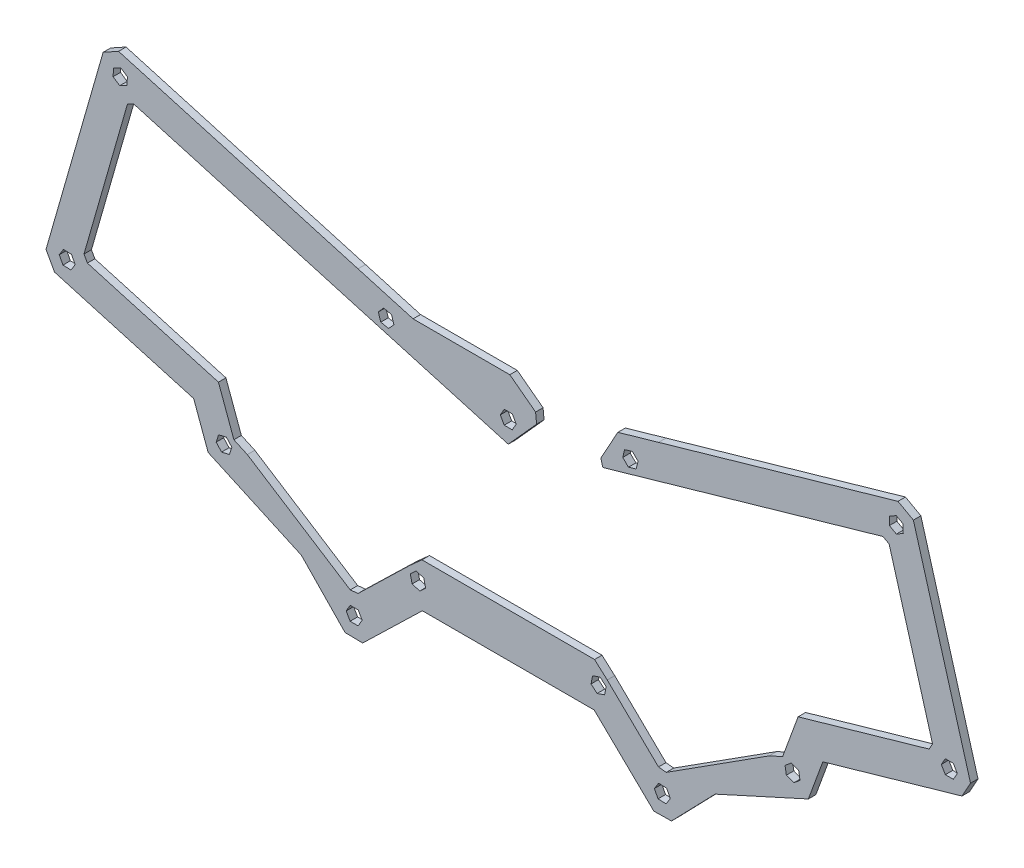
SolidWorks part; units mm, degrees
ref_plane "Plan de face" through (0, 0, 0) normal (0, 0, 1) x (1, 0, 0)
ref_plane "Plan de dessus" through (0, 0, 0) normal (0, 1, 0) x (1, 0, 0)
ref_plane "Plan de droite" through (0, 0, 0) normal (1, 0, 0) x (0, 0, -1)
sketch "Esquisse1" plane through (0, 0, 0) normal (0, 0, 1) x (1, 0, 0)
  line L0 (-121.6461, -32.0475) -> (-108.1875, -28.1884) construction
  line L1 (-108.1875, -28.1884) -> (-104.3283, -41.647) construction
  line L2 (-104.3283, -41.647) -> (-117.7869, -45.5062) construction
  line L3 (-117.7869, -45.5062) -> (-121.6461, -32.0475) construction
  line L4 (-100.1763, -37.9855) -> (-104.0355, -24.5269) construction
  line L5 (-104.0355, -24.5269) -> (-90.5769, -20.6677) construction
  line L6 (-90.5769, -20.6677) -> (-86.7177, -34.1263) construction
  line L7 (-86.7177, -34.1263) -> (-100.1763, -37.9855) construction
  line L8 (-82.5657, -30.4649) -> (-86.4249, -17.0063) construction
  line L9 (-86.4249, -17.0063) -> (-72.9663, -13.1471) construction
  line L10 (-72.9663, -13.1471) -> (-69.1071, -26.6057) construction
  line L11 (-69.1071, -26.6057) -> (-82.5657, -30.4649) construction
  line L12 (-63.6458, -27.5106) -> (-67.505, -14.0519) construction
  line L13 (-67.505, -14.0519) -> (-54.0463, -10.1927) construction
  line L14 (-54.0463, -10.1927) -> (-50.1872, -23.6514) construction
  line L15 (-50.1872, -23.6514) -> (-63.6458, -27.5106) construction
  line L16 (-44.0711, -26.8394) -> (-47.9303, -13.3808) construction
  line L17 (-47.9303, -13.3808) -> (-34.4717, -9.5216) construction
  line L18 (-34.4717, -9.5216) -> (-30.6125, -22.9802) construction
  line L19 (-30.6125, -22.9802) -> (-44.0711, -26.8394) construction
  line L20 (-25.8054, -21.6018) -> (-29.6646, -8.1432) construction
  line L21 (-29.6646, -8.1432) -> (-16.206, -4.284)
  line L22 (-16.206, -4.284) -> (-12.3468, -17.7426)
  line L23 (-12.3468, -17.7426) -> (-25.8054, -21.6018) construction
  line L24 (-116.4086, -50.3128) -> (-102.95, -46.4536) construction
  line L25 (-102.95, -46.4536) -> (-99.0908, -59.9122) construction
  line L26 (-99.0908, -59.9122) -> (-112.5494, -63.7714) construction
  line L27 (-112.5494, -63.7714) -> (-116.4086, -50.3128) construction
  line L28 (-98.798, -42.7922) -> (-85.3394, -38.933) construction
  line L29 (-85.3394, -38.933) -> (-81.4802, -52.3916) construction
  line L30 (-81.4802, -52.3916) -> (-94.9388, -56.2508) construction
  line L31 (-94.9388, -56.2508) -> (-98.798, -42.7922) construction
  line L32 (-81.1874, -35.2715) -> (-67.7288, -31.4123) construction
  line L33 (-67.7288, -31.4123) -> (-63.8696, -44.8709) construction
  line L34 (-63.8696, -44.8709) -> (-77.3282, -48.7301) construction
  line L35 (-77.3282, -48.7301) -> (-81.1874, -35.2715) construction
  line L36 (-62.2675, -32.3172) -> (-48.8089, -28.458) construction
  line L37 (-48.8089, -28.458) -> (-44.9497, -41.9166) construction
  line L38 (-44.9497, -41.9166) -> (-58.4083, -45.7758) construction
  line L39 (-58.4083, -45.7758) -> (-62.2675, -32.3172) construction
  line L40 (-42.6928, -31.646) -> (-29.2342, -27.7869) construction
  line L41 (-29.2342, -27.7869) -> (-25.375, -41.2455) construction
  line L42 (-25.375, -41.2455) -> (-38.8336, -45.1047) construction
  line L43 (-38.8336, -45.1047) -> (-42.6928, -31.646) construction
  line L44 (-24.4271, -26.4084) -> (-10.9685, -22.5492) construction
  line L45 (-10.9685, -22.5492) -> (-7.1093, -36.0078) construction
  line L46 (-7.1093, -36.0078) -> (-20.5679, -39.867) construction
  line L47 (-20.5679, -39.867) -> (-24.4271, -26.4084) construction
  line L48 (-19.1896, -44.6737) -> (-5.731, -40.8145) construction
  line L49 (-5.731, -40.8145) -> (-1.8718, -54.2731) construction
  line L50 (-1.8718, -54.2731) -> (-15.3304, -58.1323) construction
  line L51 (-15.3304, -58.1323) -> (-19.1896, -44.6737) construction
  line L52 (-37.4554, -49.9113) -> (-23.9967, -46.0521) construction
  line L53 (-23.9967, -46.0521) -> (-20.1376, -59.5107) construction
  line L54 (-20.1376, -59.5107) -> (-33.5962, -63.3699) construction
  line L55 (-33.5962, -63.3699) -> (-37.4554, -49.9113) construction
  line L56 (-57.03, -50.5825) -> (-43.5714, -46.7233) construction
  line L57 (-43.5714, -46.7233) -> (-39.7122, -60.1819) construction
  line L58 (-39.7122, -60.1819) -> (-53.1708, -64.0411) construction
  line L59 (-53.1708, -64.0411) -> (-57.03, -50.5825) construction
  line L60 (-75.9499, -53.5368) -> (-62.4913, -49.6776) construction
  line L61 (-62.4913, -49.6776) -> (-58.6321, -63.1362) construction
  line L62 (-58.6321, -63.1362) -> (-72.0908, -66.9954) construction
  line L63 (-72.0908, -66.9954) -> (-75.9499, -53.5368) construction
  line L64 (-93.5605, -61.0574) -> (-80.1019, -57.1982) construction
  line L65 (-80.1019, -57.1982) -> (-76.2427, -70.6569) construction
  line L66 (-76.2427, -70.6569) -> (-89.7013, -74.516) construction
  line L67 (-89.7013, -74.516) -> (-93.5605, -61.0574) construction
  line L68 (-111.1711, -68.5781) -> (-97.7125, -64.7189) construction
  line L69 (-97.7125, -64.7189) -> (-93.8533, -78.1775) construction
  line L70 (-93.8533, -78.1775) -> (-107.3119, -82.0367) construction
  line L71 (-107.3119, -82.0367) -> (-111.1711, -68.5781) construction
  line L72 (-79.0181, -77.3048) -> (-65.5595, -73.4456) construction
  line L73 (-65.5595, -73.4456) -> (-61.7003, -86.9042) construction
  line L74 (-61.7003, -86.9042) -> (-75.1589, -90.7634) construction
  line L75 (-75.1589, -90.7634) -> (-79.0181, -77.3048) construction
  line L76 (-99.4001, -88.1351) -> (-87.3916, -80.9362) construction
  line L77 (-87.3916, -80.9362) -> (-80.1927, -92.9448) construction
  line L78 (-80.1927, -92.9448) -> (-92.2012, -100.1436) construction
  line L79 (-92.2012, -100.1436) -> (-99.4001, -88.1351) construction
  line L80 (-120.0498, -100.4367) -> (-110.317, -90.3719) construction
  line L81 (-110.317, -90.3719) -> (-100.2522, -100.1047) construction
  line L82 (-100.2522, -100.1047) -> (-109.985, -110.1695) construction
  line L83 (-109.985, -110.1695) -> (-120.0498, -100.4367) construction
  line L86 (0.634, -55.7756) -> (-52.9527, -71.1413) construction
  line L89 (-59.2205, -88.2424) -> (-52.9527, -71.1413) construction
  line L96 (-93.4066, -103.0586) -> (-59.4637, -88.3612) construction
  line L97 (-105.418, -115.2057) -> (-93.9754, -103.3509) construction
  line L98 (-126.5332, -96.9919) -> (-107.5003, -115.385) construction
  line L99 (-167.7972, -50.1766) -> (-183.2082, -64.014) construction
  line L100 (-106.3822, -25.4572) -> (-123.6848, -30.4187) construction
  line L101 (-72.1178, -10.6906) -> (-88.4663, -15.3784) construction
  line L102 (-53.2337, -7.6163) -> (-70.5393, -12.5786) construction
  line L103 (-33.6604, -6.9452) -> (-50.9661, -11.9075) construction
  line L104 (-15.3965, -1.7081) -> (-31.745, -6.396) construction
  line L105 (0.5403, -55.2132) -> (-14.6896, -2.0999) construction
  line L106 (-16.199, -60.6113) -> (0.1495, -55.9235) construction
  line L107 (-52.7198, -71.0835) -> (-18.1144, -61.1606) construction
  line L108 (-59.1184, -88.0534) -> (-52.9674, -71.2752) construction
  line L109 (-183.2082, -64.014) -> (-173.1824, -64.9357) construction
  line L113 (-102.2678, -134.438) -> (-84.7238, -116.3191)
  line L114 (-84.7238, -116.3191) -> (-47.2969, -99.2981)
  line L115 (-47.2969, -99.2981) -> (-41.4917, -83.4594)
  line L116 (14.3812, -67.4381) -> (-41.4917, -83.4594)
  line L117 (17.8093, -61.2536) -> (-5.1371, 18.7701)
  line L122 (-11.3217, 22.1985) -> (-107.4545, -5.3614)
  line L129 (-167.7953, -27.6055) -> (-167.7953, -64.7189) construction
  line L130 (-242.0685, -103.8419) -> (-276.37, -88.2424) construction
  line L131 (-229.5108, -116.8112) -> (-242.0685, -103.8419) construction
  line L138 (-208.9328, -96.8551) -> (-229.5108, -116.8112) construction
  line L139 (-225.5107, -79.6567) -> (-208.9328, -96.8551) construction
  line L140 (-109.3352, -134.5492) -> (-102.2678, -134.438)
  line L142 (-5.1371, 18.7701) -> (-11.3217, 22.1985)
  line L143 (-211.4691, -30.6868) -> (-225.5107, -79.6567) construction
  line L147 (-114.18, -7.2899) -> (-107.4545, -5.3614)
  line L148 (-114.18, -7.2899) -> (-123.7936, -10.0465)
  line L154 (-4.3102, 15.8863) -> (-127.3606, -19.3904) construction
  line L155 (-131.531, -101.8802) -> (-105.9239, -126.7133) construction
  line L156 (-105.9239, -126.7133) -> (-89.4162, -109.6646) construction
  line L157 (-127.3539, -97.573) -> (-105.9069, -118.3718) construction
  line L158 (-105.9069, -118.3718) -> (-63.5032, -91.2886) construction
  line L159 (-63.5032, -91.2886) -> (-58.4256, -88.9794) construction
  line L160 (-58.4256, -88.9794) -> (-52.1886, -71.9625) construction
  line L161 (1.8709, -56.4612) -> (-52.1886, -71.9625) construction
  line L162 (1.8709, -56.4612) -> (-14.1861, -0.4639) construction
  line L163 (-14.1861, -0.4639) -> (-50.7166, -10.9388) construction
  line L164 (-50.7166, -10.9388) -> (-52.026, -6.3725) construction
  line L165 (-52.026, -6.3725) -> (-70.2913, -11.61) construction
  line L166 (-70.2913, -11.61) -> (-70.911, -9.4488) construction
  line L167 (-70.911, -9.4488) -> (-90.1377, -14.9608) construction
  line L168 (-90.1377, -14.9608) -> (-89.5177, -17.1231) construction
  line L169 (-89.5177, -17.1231) -> (-107.783, -22.3606) construction
  line L170 (-107.783, -22.3606) -> (-107.0938, -24.7639) construction
  line L171 (-107.0938, -24.7639) -> (-125.3583, -30.0011) construction
  line L172 (-125.3583, -30.0011) -> (-111.0411, -79.9324) construction
  line L173 (-110.7998, -78.9627) -> (-127.3777, -96.1611) construction
  line L174 (-89.4162, -109.6646) -> (-53.6562, -93.4017) construction
  line L175 (-53.6562, -93.4017) -> (-47.6042, -76.8897) construction
  line L176 (9.2923, -60.5749) -> (-47.6042, -76.8897) construction
  line L177 (9.2923, -60.5749) -> (-12.0005, 13.6817) construction
  line L178 (-229.7336, -25.4495) -> (-211.4691, -30.6868) construction
  line L179 (-229.0444, -23.0462) -> (-229.7336, -25.4495) construction
  line L180 (-173.1824, -64.9357) -> (-167.7972, -60.1004) construction
  line L181 (-247.3097, -17.8087) -> (-229.0444, -23.0462) construction
  line L185 (17.8093, -61.2536) -> (14.3812, -67.4381)
  line L186 (-183.2987, -65.7677) -> (-173.2729, -66.6895) construction
  line L187 (-173.2729, -66.6895) -> (-167.8052, -74.7882) construction
  line L190 (-246.6897, -15.6465) -> (-247.3097, -17.8087) construction
  line L191 (-263.9939, -10.6857) -> (-246.6897, -15.6465) construction
  line L192 (-264.6136, -12.8469) -> (-263.9939, -10.6857) construction
  line L193 (-282.8789, -7.6094) -> (-264.6136, -12.8469) construction
  line L194 (-284.1883, -12.1757) -> (-282.8789, -7.6094) construction
  line L195 (-320.7188, -1.7008) -> (-284.1883, -12.1757) construction
  line L196 (-336.2245, -55.7756) -> (-320.7188, -1.7008) construction
  line L197 (-183.2987, -65.7677) -> (-167.8052, -88.0782) construction
  line L198 (-181.8414, -71.5322) -> (-174.8684, -81.0171) construction
  line L199 (-174.8684, -81.0171) -> (-178.3549, -83.9622) construction
  line L200 (-344.8828, -60.5749) -> (-323.5901, 13.6817) construction
  line L201 (-344.8828, -60.5749) -> (-287.9863, -76.8897) construction
  line L202 (-281.9343, -93.4017) -> (-287.9863, -76.8897) construction
  line L203 (-246.1743, -109.6646) -> (-281.9343, -93.4017) construction
  line L204 (-224.7907, -78.9627) -> (-208.2128, -96.1611) construction
  line L205 (-210.2322, -30.0011) -> (-224.5494, -79.9324) construction
  line L206 (-228.4967, -24.7639) -> (-210.2322, -30.0011) construction
  line L207 (-227.8075, -22.3606) -> (-228.4967, -24.7639) construction
  line L208 (-246.0728, -17.1231) -> (-227.8075, -22.3606) construction
  line L209 (-245.4528, -14.9608) -> (-246.0728, -17.1231) construction
  line L210 (-264.6796, -9.4488) -> (-245.4528, -14.9608) construction
  line L211 (-265.2993, -11.61) -> (-264.6796, -9.4488) construction
  line L212 (-283.5645, -6.3725) -> (-265.2993, -11.61) construction
  line L213 (-284.8739, -10.9388) -> (-283.5645, -6.3725) construction
  line L217 (0.634, -55.7756) -> (-14.8717, -1.7008) construction
  line L220 (-14.8717, -1.7008) -> (-51.4022, -12.1757) construction
  line L221 (-51.4022, -12.1757) -> (-52.7116, -7.6094) construction
  line L222 (-52.7116, -7.6094) -> (-70.9769, -12.8469) construction
  line L223 (-70.9769, -12.8469) -> (-71.5966, -10.6857) construction
  line L224 (-71.5966, -10.6857) -> (-88.9008, -15.6465) construction
  line L225 (-88.9008, -15.6465) -> (-88.2808, -17.8087) construction
  line L226 (-88.2808, -17.8087) -> (-106.5461, -23.0462) construction
  line L227 (-106.5461, -23.0462) -> (-105.8569, -25.4495) construction
  line L228 (-105.8569, -25.4495) -> (-124.1214, -30.6868) construction
  line L231 (-124.1214, -30.6868) -> (-110.0799, -79.6567) construction
  line L232 (-110.0799, -79.6567) -> (-126.6577, -96.8551) construction
  line L233 (-126.6577, -96.8551) -> (-106.0797, -116.8112) construction
  line L234 (-106.0797, -116.8112) -> (-93.522, -103.8419) construction
  line L235 (-93.522, -103.8419) -> (-59.2205, -88.2424) construction
  line L236 (-321.4044, -0.4639) -> (-284.8739, -10.9388) construction
  line L237 (-337.4614, -56.4612) -> (-321.4044, -0.4639) construction
  line L238 (-337.4614, -56.4612) -> (-283.4019, -71.9625) construction
  line L239 (-277.1649, -88.9794) -> (-283.4019, -71.9625) construction
  line L240 (-272.0873, -91.2886) -> (-277.1649, -88.9794) construction
  line L241 (-229.6837, -118.3718) -> (-272.0873, -91.2886) construction
  line L242 (-208.2366, -97.573) -> (-229.6837, -118.3718) construction
  line L243 (-229.6666, -126.7133) -> (-246.1743, -109.6646) construction
  line L244 (-204.0596, -101.8802) -> (-229.6666, -126.7133) construction
  line L245 (-331.2803, 15.8863) -> (-208.2299, -19.3904) construction
  line L246 (-178.3549, -83.9622) -> (-185.8788, -75.0552) construction
  line L247 (-185.8788, -75.0552) -> (-181.8414, -71.5322) construction
  line L248 (-176.7625, -46.6332) -> (-185.5498, -54.5291) construction
  line L249 (-185.5498, -54.5291) -> (-181.1562, -59.4188) construction
  line L250 (-181.1562, -59.4188) -> (-172.3689, -51.5229) construction
  line L251 (-276.4721, -88.0534) -> (-282.6232, -71.2752) construction
  line L252 (-282.8707, -71.0835) -> (-317.4761, -61.1606) construction
  line L253 (-319.3915, -60.6113) -> (-335.74, -55.9235) construction
  line L254 (-336.1309, -55.2132) -> (-320.9009, -2.0999) construction
  line L255 (-320.194, -1.7081) -> (-303.8455, -6.396) construction
  line L256 (-301.9301, -6.9452) -> (-284.6245, -11.9075) construction
  line L257 (-282.3568, -7.6163) -> (-265.0512, -12.5786) construction
  line L258 (-263.4727, -10.6906) -> (-247.1242, -15.3784) construction
  line L259 (-229.2083, -25.4572) -> (-211.9057, -30.4187) construction
  line L260 (-172.3689, -51.5229) -> (-176.7625, -46.6332) construction
  line L261 (-209.0573, -96.9919) -> (-228.0902, -115.385) construction
  line L262 (-230.1725, -115.2057) -> (-241.6151, -103.3509) construction
  line L263 (-242.1839, -103.0586) -> (-276.1268, -88.3612) construction
  line L264 (-276.37, -88.2424) -> (-282.6379, -71.1413) construction
  line L265 (-336.2245, -55.7756) -> (-282.6379, -71.1413) construction
  line L268 (-353.3998, -61.2536) -> (-349.9717, -67.4381)
  line L274 (-221.4105, -7.2899) -> (-206.0252, -11.7015)
  line L275 (-221.4105, -7.2899) -> (-228.136, -5.3614)
  line L276 (-330.4534, 18.7701) -> (-324.2688, 22.1985)
  line L277 (-226.2553, -134.5492) -> (-233.3227, -134.438)
  line L281 (-324.2688, 22.1985) -> (-228.136, -5.3614)
  line L282 (-353.3998, -61.2536) -> (-330.4534, 18.7701)
  line L283 (-349.9717, -67.4381) -> (-294.0988, -83.4594)
  line L284 (-288.2936, -99.2981) -> (-294.0988, -83.4594)
  line L285 (-250.8667, -116.3191) -> (-288.2936, -99.2981)
  line L286 (-233.3227, -134.438) -> (-250.8667, -116.3191)
  line L288 (-225.6055, -110.1695) -> (-215.5407, -100.4367) construction
  line L289 (-235.3383, -100.1047) -> (-225.6055, -110.1695) construction
  line L290 (-225.2735, -90.3719) -> (-235.3383, -100.1047) construction
  line L291 (-215.5407, -100.4367) -> (-225.2735, -90.3719) construction
  line L292 (-243.3893, -100.1436) -> (-236.1904, -88.1351) construction
  line L293 (-255.3978, -92.9448) -> (-243.3893, -100.1436) construction
  line L294 (-248.1989, -80.9362) -> (-255.3978, -92.9448) construction
  line L295 (-236.1904, -88.1351) -> (-248.1989, -80.9362) construction
  line L296 (-260.4316, -90.7634) -> (-256.5724, -77.3048) construction
  line L297 (-273.8902, -86.9042) -> (-260.4316, -90.7634) construction
  line L298 (-270.031, -73.4456) -> (-273.8902, -86.9042) construction
  line L299 (-256.5724, -77.3048) -> (-270.031, -73.4456) construction
  line L300 (-228.2786, -82.0367) -> (-224.4194, -68.5781) construction
  line L301 (-241.7372, -78.1775) -> (-228.2786, -82.0367) construction
  line L302 (-237.878, -64.7189) -> (-241.7372, -78.1775) construction
  line L303 (-224.4194, -68.5781) -> (-237.878, -64.7189) construction
  line L304 (-245.8892, -74.516) -> (-242.03, -61.0574) construction
  line L305 (-259.3478, -70.6569) -> (-245.8892, -74.516) construction
  line L306 (-255.4886, -57.1982) -> (-259.3478, -70.6569) construction
  line L307 (-242.03, -61.0574) -> (-255.4886, -57.1982) construction
  line L308 (-263.4998, -66.9954) -> (-259.6406, -53.5368) construction
  line L309 (-276.9584, -63.1362) -> (-263.4998, -66.9954) construction
  line L310 (-273.0992, -49.6776) -> (-276.9584, -63.1362) construction
  line L311 (-259.6406, -53.5368) -> (-273.0992, -49.6776)
  line L312 (-282.4197, -64.0411) -> (-278.5605, -50.5825) construction
  line L313 (-295.8783, -60.1819) -> (-282.4197, -64.0411) construction
  line L314 (-292.0191, -46.7233) -> (-295.8783, -60.1819) construction
  line L315 (-278.5605, -50.5825) -> (-292.0191, -46.7233) construction
  line L316 (-301.9944, -63.3699) -> (-298.1352, -49.9113) construction
  line L317 (-315.453, -59.5107) -> (-301.9944, -63.3699) construction
  line L318 (-311.5938, -46.0521) -> (-315.453, -59.5107) construction
  line L319 (-298.1352, -49.9113) -> (-311.5938, -46.0521) construction
  line L320 (-320.2601, -58.1323) -> (-316.4009, -44.6737) construction
  line L321 (-333.7187, -54.2731) -> (-320.2601, -58.1323) construction
  line L322 (-329.8595, -40.8145) -> (-333.7187, -54.2731) construction
  line L323 (-316.4009, -44.6737) -> (-329.8595, -40.8145) construction
  line L324 (-315.0226, -39.867) -> (-311.1634, -26.4084) construction
  line L325 (-328.4812, -36.0078) -> (-315.0226, -39.867) construction
  line L326 (-324.622, -22.5492) -> (-328.4812, -36.0078) construction
  line L327 (-311.1634, -26.4084) -> (-324.622, -22.5492) construction
  line L328 (-296.7569, -45.1047) -> (-292.8977, -31.646) construction
  line L329 (-310.2155, -41.2455) -> (-296.7569, -45.1047) construction
  line L330 (-306.3563, -27.7869) -> (-310.2155, -41.2455) construction
  line L331 (-292.8977, -31.646) -> (-306.3563, -27.7869) construction
  line L332 (-277.1822, -45.7758) -> (-273.323, -32.3172) construction
  line L333 (-290.6408, -41.9166) -> (-277.1822, -45.7758) construction
  line L334 (-286.7817, -28.458) -> (-290.6408, -41.9166) construction
  line L335 (-273.323, -32.3172) -> (-286.7817, -28.458) construction
  line L336 (-258.2623, -48.7301) -> (-254.4031, -35.2715) construction
  line L337 (-271.7209, -44.8709) -> (-258.2623, -48.7301) construction
  line L338 (-267.8617, -31.4123) -> (-271.7209, -44.8709) construction
  line L339 (-254.4031, -35.2715) -> (-267.8617, -31.4123) construction
  line L340 (-240.6517, -56.2508) -> (-236.7925, -42.7922) construction
  line L341 (-254.1103, -52.3916) -> (-240.6517, -56.2508) construction
  line L342 (-250.2511, -38.933) -> (-254.1103, -52.3916) construction
  line L343 (-236.7925, -42.7922) -> (-250.2511, -38.933) construction
  line L344 (-223.0411, -63.7714) -> (-219.1819, -50.3128) construction
  line L345 (-236.4997, -59.9122) -> (-223.0411, -63.7714) construction
  line L346 (-232.6405, -46.4536) -> (-236.4997, -59.9122) construction
  line L347 (-219.1819, -50.3128) -> (-232.6405, -46.4536) construction
  line L348 (-323.2438, -17.7426) -> (-309.7851, -21.6018) construction
  line L349 (-319.3846, -4.284) -> (-323.2438, -17.7426) construction
  line L350 (-305.926, -8.1432) -> (-319.3846, -4.284) construction
  line L351 (-309.7851, -21.6018) -> (-305.926, -8.1432) construction
  line L352 (-304.978, -22.9802) -> (-291.5194, -26.8394) construction
  line L353 (-301.1188, -9.5216) -> (-304.978, -22.9802) construction
  line L354 (-287.6602, -13.3808) -> (-301.1188, -9.5216) construction
  line L355 (-291.5194, -26.8394) -> (-287.6602, -13.3808) construction
  line L356 (-285.4034, -23.6514) -> (-271.9448, -27.5106) construction
  line L357 (-281.5442, -10.1927) -> (-285.4034, -23.6514) construction
  line L358 (-268.0856, -14.0519) -> (-281.5442, -10.1927) construction
  line L359 (-271.9448, -27.5106) -> (-268.0856, -14.0519) construction
  line L360 (-266.4834, -26.6057) -> (-253.0248, -30.4649) construction
  line L361 (-262.6242, -13.1471) -> (-266.4834, -26.6057) construction
  line L362 (-249.1656, -17.0063) -> (-262.6242, -13.1471) construction
  line L363 (-253.0248, -30.4649) -> (-249.1656, -17.0063) construction
  line L364 (-248.8728, -34.1263) -> (-235.4142, -37.9855) construction
  line L365 (-245.0136, -20.6677) -> (-248.8728, -34.1263) construction
  line L366 (-231.555, -24.5269) -> (-245.0136, -20.6677) construction
  line L367 (-235.4142, -37.9855) -> (-231.555, -24.5269) construction
  line L368 (-217.8036, -45.5062) -> (-213.9444, -32.0475) construction
  line L369 (-231.2622, -41.647) -> (-217.8036, -45.5062) construction
  line L370 (-227.4031, -28.1884) -> (-231.2622, -41.647) construction
  line L371 (-213.9444, -32.0475) -> (-227.4031, -28.1884) construction
  line L372 (-226.2553, -134.5492) -> (-202.2968, -111.3509)
  line L373 (-109.3352, -134.5492) -> (-133.2937, -111.3509)
  line L374 (-141.5559, -103.3509) -> (-194.0347, -103.3509) construction
  line L375 (-167.7972, -50.1766) -> (-152.3861, -64.014) construction
  line L376 (-162.4119, -64.9357) -> (-167.7972, -60.1004) construction
  line L377 (-162.3376, -66.6895) -> (-167.8052, -74.7882) construction
  line L378 (-152.3118, -65.7677) -> (-167.8052, -88.0782) construction
  line L379 (-163.2254, -51.5229) -> (-158.8318, -46.6332) construction
  line L380 (-154.4381, -59.4188) -> (-163.2254, -51.5229) construction
  line L381 (-150.0445, -54.5291) -> (-154.4381, -59.4188) construction
  line L382 (-158.8318, -46.6332) -> (-150.0445, -54.5291) construction
  line L383 (-149.7316, -75.0552) -> (-153.7691, -71.5322) construction
  line L384 (-157.2555, -83.9622) -> (-149.7316, -75.0552) construction
  line L385 (-160.742, -81.0171) -> (-157.2555, -83.9622) construction
  line L386 (-153.7691, -71.5322) -> (-160.742, -81.0171) construction
  line L387 (-152.3118, -65.7677) -> (-162.3376, -66.6895) construction
  line L388 (-152.3861, -64.014) -> (-162.4119, -64.9357) construction
  line L389 (-206.0252, -11.7015) -> (-129.5654, -11.7015) construction
  line L390 (-119.0708, -62.7964) -> (-130.6498, -22.4155) construction
  line L391 (-123.5545, -47.16) -> (-127.4136, -33.7014) construction
  line L392 (-120.442, -65.2702) -> (-138.2688, -70.3819) construction
  line L393 (-140.7426, -69.0107) -> (-154.4194, -21.3141) construction
  line L394 (-167.1758, -11.7015) -> (-206.0252, -11.7015)
  line L395 (-156.8153, -19.5087) -> (-167.1758, -11.7015)
  line L396 (-123.7936, -10.0465) -> (-130.6498, -22.4155)
  line L397 (-138.2688, -70.3819) -> (-140.7426, -69.0107) construction
  line L398 (-119.0708, -62.7964) -> (-120.442, -65.2702) construction
  line L399 (-129.5654, -11.7015) -> (-123.7936, -10.0465) construction
  line L400 (-207.5404, -98.2908) -> (-228.1196, -118.248)
  line L401 (-231.2409, -118.5638) -> (-272.5658, -92.1695)
  line L402 (-272.5658, -92.1695) -> (-277.9598, -89.7165)
  line L403 (-277.9598, -89.7165) -> (-284.166, -72.7837)
  line L404 (-336.7758, -57.6981) -> (-284.166, -72.7837)
  line L405 (-338.147, -55.2243) -> (-320.7131, 5.5749)
  line L406 (-223.5881, -80.208) -> (-202.439, -93.7159) construction
  line L407 (-202.439, -93.7159) -> (-207.5404, -98.2908)
  line L408 (-17.3512, 6.9463) -> (-127.905, -24.7479)
  line L409 (2.5565, -55.2243) -> (-14.8774, 5.5749)
  line L410 (-318.2393, 6.9463) -> (-167.7953, -36.1838)
  line L411 (1.1853, -57.6981) -> (-51.4245, -72.7837)
  line L412 (-57.6307, -89.7165) -> (-51.4245, -72.7837)
  line L413 (-63.0247, -92.1695) -> (-57.6307, -89.7165)
  line L414 (-104.3497, -118.5638) -> (-63.0247, -92.1695)
  line L415 (-207.6856, -24.7479) -> (-223.5881, -80.208) construction
  line L416 (-338.6983, -57.1468) -> (-322.0901, 0.773) construction
  line L417 (-265.3652, -8.212) -> (-244.2159, -14.2752) construction
  line L418 (-208.9953, -29.3155) -> (-223.5881, -80.208) construction
  line L419 (-227.2598, -24.0783) -> (-208.9953, -29.3155) construction
  line L420 (-226.5706, -21.6749) -> (-227.2598, -24.0783) construction
  line L421 (-244.8359, -16.4375) -> (-226.5706, -21.6749) construction
  line L422 (-244.2159, -14.2752) -> (-244.8359, -16.4375) construction
  line L423 (-265.9849, -10.3731) -> (-265.3652, -8.212) construction
  line L424 (-284.2502, -5.1356) -> (-265.9849, -10.3731) construction
  line L425 (-285.5595, -9.7019) -> (-284.2502, -5.1356) construction
  line L426 (-322.0901, 0.773) -> (-285.5595, -9.7019) construction
  line L427 (-128.0501, -98.2908) -> (-107.4709, -118.248)
  line L428 (-133.1515, -93.7159) -> (-128.0501, -98.2908)
  line L429 (-127.905, -24.7479) -> (-167.7953, -36.1862) construction
  line L430 (-129.8233, -25.2979) -> (-130.6498, -22.4155)
  line L431 (-202.439, -93.7159) -> (-133.1515, -93.7159)
  line L432 (-167.7953, -36.1838) -> (-156.4257, -23.5445)
  line L433 (-129.8233, -25.2979) -> (-127.905, -24.7479)
  line L434 (-156.4257, -23.5445) -> (-156.8153, -19.5087)
  line L435 (-320.7131, 5.5749) -> (-318.2393, 6.9463)
  line L436 (-338.6983, -57.1468) -> (-284.166, -72.7837) construction
  line L437 (-338.147, -55.2243) -> (-336.7758, -57.6981)
  line L438 (-207.5404, -98.2908) -> (-229.5553, -119.6404) construction
  line L439 (-229.5553, -119.6404) -> (-272.5658, -92.1695) construction
  line L440 (-228.1196, -118.248) -> (-231.2409, -118.5638)
  line L441 (-107.4709, -118.248) -> (-104.3497, -118.5638)
  line L442 (2.5565, -55.2243) -> (1.1853, -57.6981)
  line L443 (-14.8774, 5.5749) -> (-17.3512, 6.9463)
  line L444 (-133.2937, -111.3509) -> (-202.2968, -111.3509)
  line L445 (-214.6968, -14.5277) -> (-217.8401, -13.8763)
  line L446 (-217.8401, -13.8763) -> (-219.9759, -16.2728)
  line L447 (-219.9759, -16.2728) -> (-218.9683, -19.3206)
  line L448 (-218.9683, -19.3206) -> (-215.8251, -19.972)
  line L449 (-215.8251, -19.972) -> (-213.6893, -17.5755)
  line L450 (-213.6893, -17.5755) -> (-214.6968, -14.5277)
  line L451 (-166.1757, -24.834) -> (-169.3858, -24.8172)
  line L452 (-169.3858, -24.8172) -> (-171.0053, -27.5888)
  line L453 (-171.0053, -27.5888) -> (-169.4148, -30.3771)
  line L454 (-169.4148, -30.3771) -> (-166.2047, -30.3939)
  line L455 (-166.2047, -30.3939) -> (-164.5852, -27.6223)
  line L456 (-164.5852, -27.6223) -> (-166.1757, -24.834)
  line L457 (-115.6722, -16.0395) -> (-117.9812, -13.8095)
  line L458 (-117.9812, -13.8095) -> (-121.0669, -14.6941)
  line L459 (-121.0669, -14.6941) -> (-121.8437, -17.8088)
  line L460 (-121.8437, -17.8088) -> (-119.5347, -20.0388)
  line L461 (-119.5347, -20.0388) -> (-116.4489, -19.1542)
  line L462 (-116.4489, -19.1542) -> (-115.6722, -16.0395)
  line L463 (-9.2401, 15.3202) -> (-12.0393, 16.8915)
  line L464 (-12.0393, 16.8915) -> (-14.7996, 15.253)
  line L465 (-14.7996, 15.253) -> (-14.7608, 12.0431)
  line L466 (-14.7608, 12.0431) -> (-11.9616, 10.4718)
  line L467 (-11.9616, 10.4718) -> (-9.2013, 12.1103)
  line L468 (-9.2013, 12.1103) -> (-9.2401, 15.3202)
  line L469 (12.5024, -60.5749) -> (10.8973, -57.7949)
  line L470 (10.8973, -57.7949) -> (7.6873, -57.7949)
  line L471 (7.6873, -57.7949) -> (6.0822, -60.5749)
  line L472 (6.0822, -60.5749) -> (7.6873, -63.3549)
  line L473 (7.6873, -63.3549) -> (10.8973, -63.3549)
  line L474 (10.8973, -63.3549) -> (12.5024, -60.5749)
  line L475 (-50.6498, -94.5269) -> (-51.1786, -91.3606)
  line L476 (-51.1786, -91.3606) -> (-54.185, -90.2355)
  line L477 (-54.185, -90.2355) -> (-56.6626, -92.2765)
  line L478 (-56.6626, -92.2765) -> (-56.1338, -95.4427)
  line L479 (-56.1338, -95.4427) -> (-53.1274, -96.5679)
  line L480 (-53.1274, -96.5679) -> (-50.6498, -94.5269)
  line L481 (-104.4402, -129.5599) -> (-102.7168, -126.8517)
  line L482 (-102.7168, -126.8517) -> (-104.2006, -124.0051)
  line L483 (-104.2006, -124.0051) -> (-107.4076, -123.8667)
  line L484 (-107.4076, -123.8667) -> (-109.131, -126.575)
  line L485 (-109.131, -126.575) -> (-107.6473, -129.4216)
  line L486 (-107.6473, -129.4216) -> (-104.4402, -129.5599)
  line L487 (-132.1348, -105.033) -> (-129.1025, -103.9795)
  line L488 (-129.1025, -103.9795) -> (-128.4987, -100.8268)
  line L489 (-128.4987, -100.8268) -> (-130.9271, -98.7274)
  line L490 (-130.9271, -98.7274) -> (-133.9594, -99.7809)
  line L491 (-133.9594, -99.7809) -> (-134.5633, -102.9336)
  line L492 (-134.5633, -102.9336) -> (-132.1348, -105.033)
  line L493 (-200.9863, -102.8073) -> (-201.7201, -99.6822)
  line L494 (-201.7201, -99.6822) -> (-204.7933, -98.7551)
  line L495 (-204.7933, -98.7551) -> (-207.1328, -100.9531)
  line L496 (-207.1328, -100.9531) -> (-206.3991, -104.0782)
  line L497 (-206.3991, -104.0782) -> (-203.3258, -105.0053)
  line L498 (-203.3258, -105.0053) -> (-200.9863, -102.8073)
  line L499 (-228.0726, -129.4997) -> (-226.4565, -126.726)
  line L500 (-226.4565, -126.726) -> (-228.0506, -123.9397)
  line L501 (-228.0506, -123.9397) -> (-231.2606, -123.927)
  line L502 (-231.2606, -123.927) -> (-232.8766, -126.7006)
  line L503 (-232.8766, -126.7006) -> (-231.2826, -129.4869)
  line L504 (-231.2826, -129.4869) -> (-228.0726, -129.4997)
  line L505 (-279.7615, -95.7646) -> (-278.8016, -92.7014)
  line L506 (-278.8016, -92.7014) -> (-280.9744, -90.3385)
  line L507 (-280.9744, -90.3385) -> (-284.1072, -91.0388)
  line L508 (-284.1072, -91.0388) -> (-285.0671, -94.102)
  line L509 (-285.0671, -94.102) -> (-282.8943, -96.4649)
  line L510 (-282.8943, -96.4649) -> (-279.7615, -95.7646)
  line L511 (-343.3818, -63.4124) -> (-341.6749, -60.6938)
  line L512 (-341.6749, -60.6938) -> (-343.176, -57.8563)
  line L513 (-343.176, -57.8563) -> (-346.3838, -57.7374)
  line L514 (-346.3838, -57.7374) -> (-348.0907, -60.4561)
  line L515 (-348.0907, -60.4561) -> (-346.5896, -63.2936)
  line L516 (-346.5896, -63.2936) -> (-343.3818, -63.4124)
  line L517 (-323.3776, 16.8847) -> (-326.2578, 15.4671)
  line L518 (-326.2578, 15.4671) -> (-326.4702, 12.2641)
  line L519 (-326.4702, 12.2641) -> (-323.8025, 10.4786)
  line L520 (-323.8025, 10.4786) -> (-320.9224, 11.8962)
  line L521 (-320.9224, 11.8962) -> (-320.7099, 15.0992)
  line L522 (-320.7099, 15.0992) -> (-323.3776, 16.8847)
  line L523 (-141.5559, -111.3509) -> (-194.0347, -111.3509) construction
  circle A2 centre (-12.0005, 13.6817) radius 1.6 construction
  circle A3 centre (-12.0005, 13.6817) radius 3 construction
  circle A4 centre (-118.7579, -16.9241) radius 1.6 construction
  circle A5 centre (9.2923, -60.5749) radius 1.6 construction
  circle A6 centre (-53.6562, -93.4017) radius 1.6 construction
  circle A7 centre (-105.9239, -126.7133) radius 1.6 construction
  circle A8 centre (-131.531, -101.8802) radius 1.6 construction
  circle A10 centre (-147.4897, -45.973) radius 1.6 construction
  circle A11 centre (-323.5901, 13.6817) radius 3 construction
  circle A12 centre (-188.1008, -45.973) radius 1.6 construction
  circle A14 centre (-204.0596, -101.8802) radius 1.6 construction
  circle A15 centre (-229.6666, -126.7133) radius 1.6 construction
  circle A16 centre (-281.9343, -93.4017) radius 1.6 construction
  circle A17 centre (-344.8828, -60.5749) radius 1.6 construction
  circle A18 centre (-216.8326, -16.9241) radius 1.6 construction
  circle A19 centre (-323.5901, 13.6817) radius 1.6 construction
  circle A20 centre (-167.7953, -27.6055) radius 1.6 construction
  circle A21 centre (-216.8326, -16.9241) radius 2.78 construction
  circle A22 centre (-167.7953, -27.6055) radius 2.78 construction
  circle A23 centre (-118.7579, -16.9241) radius 2.78 construction
  circle A24 centre (-12.0005, 13.6817) radius 2.78 construction
  circle A25 centre (9.2923, -60.5749) radius 2.78 construction
  circle A26 centre (-53.6562, -93.4017) radius 2.78 construction
  circle A27 centre (-105.9239, -126.7133) radius 2.78 construction
  circle A28 centre (-131.531, -101.8802) radius 2.78 construction
  circle A29 centre (-204.0596, -101.8802) radius 2.78 construction
  circle A30 centre (-229.6666, -126.7133) radius 2.78 construction
  circle A31 centre (-281.9343, -93.4017) radius 2.78 construction
  circle A32 centre (-344.8828, -60.5749) radius 2.78 construction
  circle A33 centre (-323.5901, 13.6817) radius 2.78 construction
  point P138 (-167.7953, -27.6055)
  point P139 (-6.5153, 23.5764)
  point P150 (-169.1046, -23.0392)
  point P200 (19.1875, -66.0599)
  point P203 (-141.5228, -71.3355)
  point P204 (-141.5228, 1.5705)
  point P263 (-133.4062, -12.8029)
  point P264 (-118.5195, -64.7189)
  point P283 (-140.1914, -70.9332)
  point P284 (-157.1758, -11.7015)
  point P405 (-354.778, -66.0599)
  point P406 (-329.0752, 23.5764)
  point P423 (-15.4286, 7.4974)
  point P424 (-320.1619, 7.4974)
  point P429 (3.1078, -57.1468)
  point P434 (-106.0352, -119.6404)
  dimension "D3" = 3.2
  dimension "D4" = 6
  dimension "D6" = 3.2
  dimension "D7" = 3.2
  dimension "D8" = 3.2
  dimension "D9" = 3.2
  dimension "D10" = 3.2
  dimension "D16" = 3.2
  dimension "D21" = 5.56
  dimension "D34" = 5.56
  dimension "D2" = 6
  dimension "D5" = 1
  dimension "D11" = 5.56
  dimension "D14" = 5.56
  dimension "D22" = 5.56
  dimension "D26" = 5.56
  dimension "D27" = 5.56
  dimension "D28" = 5.56
  dimension "D29" = 5.56
  dimension "D30" = 5.56
  dimension "D31" = 5.56
  dimension "D32" = 5.56
  dimension "D33" = 5.56
  dimension "D35" = 8
extrude "Boss.-Extru.1" add sketch "Esquisse1" along normal blind 3 contours L443 L409 L442 L411 L412 L413 L414 L441 L427 L428 L431 L407 L400 L440 L401 L402 L403 L404 L437 L405 L435 L410 L432 L434 L395 L394 L274 L275 L281 L276 L282 L268 L283 L284 L285 L286 L277 L372 L374 L373 L140 L113 L114 L115 L116 L185 L117 L142 L122 L147 L148
